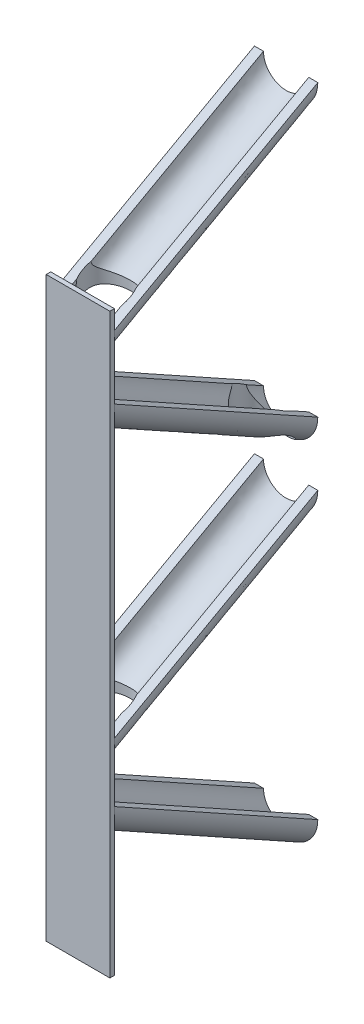
SolidWorks part; units mm, degrees
ref_plane "前基準面" through (0, 0, 0) normal (0, 0, 1) x (1, 0, 0)
ref_plane "上基準面" through (0, 0, 0) normal (0, 1, 0) x (1, 0, 0)
ref_plane "右基準面" through (0, 0, 0) normal (1, 0, 0) x (0, 0, -1)
sketch "草圖23" plane through (0, 0, 0) normal (0, 0, 1) x (1, 0, 0)
  line L0 (-5, 0) -> (-7, 0)
  line L1 (5, 0) -> (7, 0)
  arc A0 (-7, 0) -> (7, 0) centre (0, 0) ccw
  arc A1 (-5, 0) -> (5, 0) centre (0, 0) ccw
  dimension "D1" = 10
  dimension "D2" = 2
sketch "草圖24" plane through (0, 0, 0) normal (1, 0, 0) x (0, 0, -1)
  line L0 (0, -3.5) -> (-45, -28.5)
  line L1 (0, 0) -> (0, -7) construction
  dimension "D1" = 45
  dimension "D2" = 25
sweep "掃出5" add profiles "草圖23" path "草圖24"
sketch "草圖25" plane through (0, 0, 45) normal (0, 0, 1) x (1, 0, 0)
  line L0 (7, -39) -> (5, -39)
  line L1 (-5, -39) -> (-7, -39)
  arc A0 (-5, -39) -> (5, -39) centre (0, -39) ccw
  arc A1 (-7, -39) -> (7, -39) centre (0, -39) ccw
  arc A2 (-7, -25) -> (7, -25) centre (0, -25) ccw construction
  point P8 (0, -32)
  dimension "D1" = 2
  dimension "D2" = 10
  dimension "D3" = 7
sketch "草圖26" plane through (0, 0, 0) normal (1, 0, 0) x (0, 0, -1)
  line L0 (-45, -42.5) -> (0, -67.5)
  line L1 (-45, -39) -> (-45, -46) construction
  dimension "D1" = 45
  dimension "D2" = 25
sweep "掃出6" add profiles "草圖25" path "草圖26"
sketch "草圖27" plane through (0, 0, 0) normal (0, 0, -1) x (-1, 0, 0)
  line L0 (-7, -78) -> (-5, -78)
  line L1 (5, -78) -> (7, -78)
  arc A0 (-5, -78) -> (5, -78) centre (0, -78) ccw
  arc A1 (-7, -78) -> (7, -78) centre (0, -78) ccw
  arc A2 (-7, -64) -> (7, -64) centre (0, -64) ccw construction
  point P8 (0, -71)
  dimension "D1" = 2
  dimension "D2" = 10
  dimension "D3" = 7
sketch "草圖28" plane through (0, 0, 0) normal (1, 0, 0) x (0, 0, -1)
  line L0 (0, -81.5) -> (-45, -106.5)
  line L2 (0, -85) -> (0, -78) construction
  dimension "D1" = 45
  dimension "D2" = 25
sweep "掃出7" add profiles "草圖27" path "草圖28"
ref_plane "平面3" through (0, -39, 0) normal (0, 1, 0) x (1, 0, 0)
sketch "草圖29" plane through (0, -39, 0) normal (0, 1, 0) x (1, 0, 0)
  circle A0 centre (0, -5.35) radius 5.25
  point P3 (0, -5.25)
  point P4 (0, -6.5107)
  dimension "D1" = 10.5
  dimension "D2" = 5.35
sketch "草圖30" plane through (0, 0, 0) normal (0, 1, 0) x (1, 0, 0)
  circle A0 centre (0, -39.65) radius 5.25
  point P2 (0, 0)
  point P3 (0, -40.0379)
  point P4 (0, -39.8947)
  point P5 (0, -37.8904)
  point P6 (0, -39.6799)
  point P8 (0, 0)
  point P13 (0, 0)
  dimension "D1" = 10.5
  dimension "D2" = 5.35
ref_plane "平面4" through (0, -78, 0) normal (0, 1, 0) x (1, 0, 0)
sketch "草圖31" plane through (0, -78, 0) normal (0, 1, 0) x (1, 0, 0)
  circle A0 centre (0, -39.65) radius 5.25
  dimension "D1" = 10.5
sketch "草圖32" plane through (0, 0, 45) normal (0, 0, 1) x (1, 0, 0)
  line L0 (-7, -116) -> (-5, -116)
  line L1 (5, -116) -> (7, -116)
  arc A0 (-5, -116) -> (5, -116) centre (0, -116) ccw
  arc A1 (-7, -116) -> (7, -116) centre (0, -116) ccw
  arc A2 (-7, -103) -> (7, -103) centre (0, -103) ccw construction
  point P8 (0, -110)
  dimension "D1" = 10
  dimension "D2" = 2
  dimension "D3" = 6
sketch "草圖33" plane through (0, 0, 0) normal (1, 0, 0) x (0, 0, -1)
  line L0 (-45, -119.5) -> (0, -144.5)
  line L1 (-45, -116) -> (-45, -123) construction
  dimension "D1" = 45
  dimension "D2" = 25
sweep "掃出8" add profiles "草圖32" path "草圖33"
extrude "除料-伸長5" cut sketch "草圖29" against normal blind 34
extrude "除料-伸長6" cut sketch "草圖30" against normal blind 34
extrude "除料-伸長7" cut sketch "草圖31" against normal blind 34
sketch "草圖34" plane through (0, 0, 45) normal (0, 0, 1) x (1, 0, 0)
  line L0 (-7, 0) -> (-7, -25) construction
  line L1 (-7, -20.7075) -> (7.0629, -20.7075)
  line L2 (-7, -20.7075) -> (-7, -148.2671)
  line L3 (-7, -148.2671) -> (7.0629, -148.2671)
  line L4 (7.0629, -20.7075) -> (7.0629, -148.2671)
extrude "填料-伸長2" add sketch "草圖34" along normal blind 1
